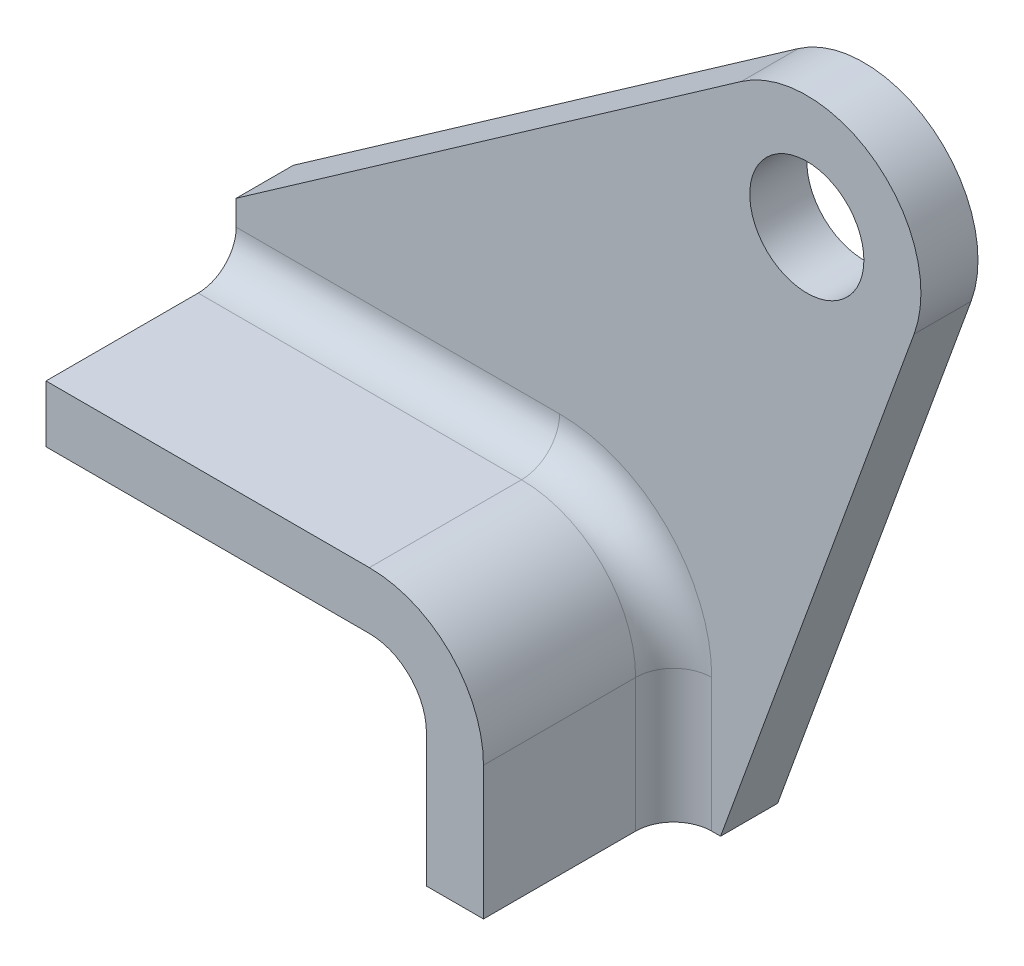
SolidWorks part; units mm, degrees
material "Простая углеродистая сталь"
ref_plane "Front" through (0, 0, 0) normal (0, 0, 1) x (1, 0, 0)
ref_plane "Top" through (0, 0, 0) normal (0, 1, 0) x (1, 0, 0)
ref_plane "Right" through (0, 0, 0) normal (1, 0, 0) x (0, 0, -1)
sketch "Эскиз1" plane through (0, 0, 0) normal (0, 0, 1) x (1, 0, 0)
  line L0 (-40, 0) -> (-6, 0)
  line L2 (10.9319, -20) -> (31.2763, 35.8958)
  line L3 (13.1171, 49.8298) -> (-40, 12.6368)
  line L4 (-40, 12.6368) -> (-40, 0)
  line L5 (0, -6) -> (0, -20)
  line L6 (0, -20) -> (10.9319, -20)
  arc A0 (31.2763, 35.8958) -> (13.1171, 49.8298) centre (20, 40) ccw
  circle A1 centre (20, 40) radius 6
  arc A2 (-6, 0) -> (0, -6) centre (-6, -6) cw
  point P16 (0, 0)
  dimension "D1" = 40
  dimension "D5" = 12
  dimension "D6" = 12
  dimension "D9" = 6
  dimension "D2" = 20
  dimension "D3" = 20
  dimension "D4" = 40
  dimension "D7" = 35
  dimension "D8" = 35
extrude "Бобышка-Вытянуть1" add sketch "Эскиз1" along normal blind 6
sketch "Эскиз2" plane through (0, 0, 6) normal (0, 0, 1) x (1, 0, 0)
  line L0 (-40, 0) -> (-6, 0) construction
  line L1 (0, -6) -> (0, -20) construction
  line L2 (-40, 0) -> (-6, 0)
  line L3 (0, -6) -> (0, -20)
  line L4 (-40, 6) -> (-6, 6)
  line L5 (6, -6) -> (6, -20)
  line L6 (0, -20) -> (6, -20)
  line L7 (-40, 0) -> (-40, 6)
  arc A0 (0, -6) -> (-6, 0) centre (-6, -6) ccw construction
  arc A1 (0, -6) -> (-6, 0) centre (-6, -6) ccw
  arc A2 (6, -6) -> (-6, 6) centre (-6, -6) ccw
  dimension "D1" = 6
extrude "Бобышка-Вытянуть2" add sketch "Эскиз2" along normal blind 20
fillet "Скругление1" radius 4 3 edges at (6, -13, 6) (2.4853, 2.4853, 6) (-23, 6, 6)
